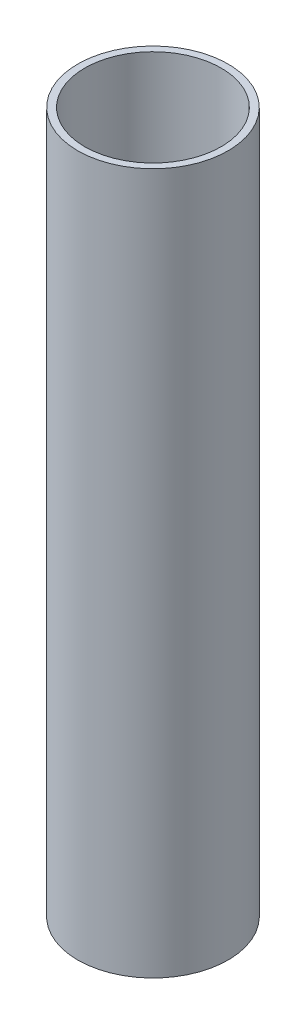
SolidWorks part; units mm, degrees
ref_plane "Front Plane" through (0, 0, 0) normal (0, 0, 1) x (1, 0, 0)
ref_plane "Top Plane" through (0, 0, 0) normal (0, 1, 0) x (1, 0, 0)
ref_plane "Right Plane" through (0, 0, 0) normal (1, 0, 0) x (0, 0, -1)
sketch "Sketch1" plane through (0, 0, 0) normal (0, 1, 0) x (1, 0, 0)
  circle A0 centre (0, 0) radius 0.56
  circle A1 centre (0, 0) radius 0.508
extrude "Boss-Extrude1" add sketch "Sketch1" along normal blind 5.22
